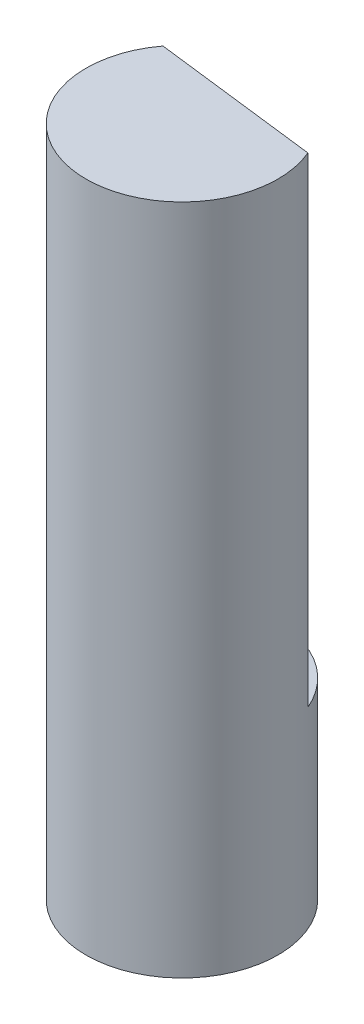
SolidWorks part; units mm, degrees
ref_plane "Front Plane" through (0, 0, 0) normal (0, 0, 1) x (1, 0, 0)
ref_plane "Top Plane" through (0, 0, 0) normal (0, 1, 0) x (1, 0, 0)
ref_plane "Right Plane" through (0, 0, 0) normal (1, 0, 0) x (0, 0, -1)
sketch "Sketch1" plane through (0, 0, 0) normal (0, 1, 0) x (1, 0, 0)
  circle A0 centre (0, 0) radius 2
extrude "Boss-Extrude1" add sketch "Sketch1" along normal blind 14
sketch "Sketch2" plane through (0, 14, 0) normal (0, 1, 0) x (1, 0, 0)
  line L0 (-1.5982, 1.2024) -> (1.8404, 0.7829)
  circle A0 centre (0, 0) radius 2 construction
  circle A1 centre (0, 0) radius 2
  circle M2 centre (0, 0) radius 2
  dimension "D1" = 1
extrude "Cut-Extrude1" cut sketch "Sketch2" against normal blind 10 contours L0 M2
